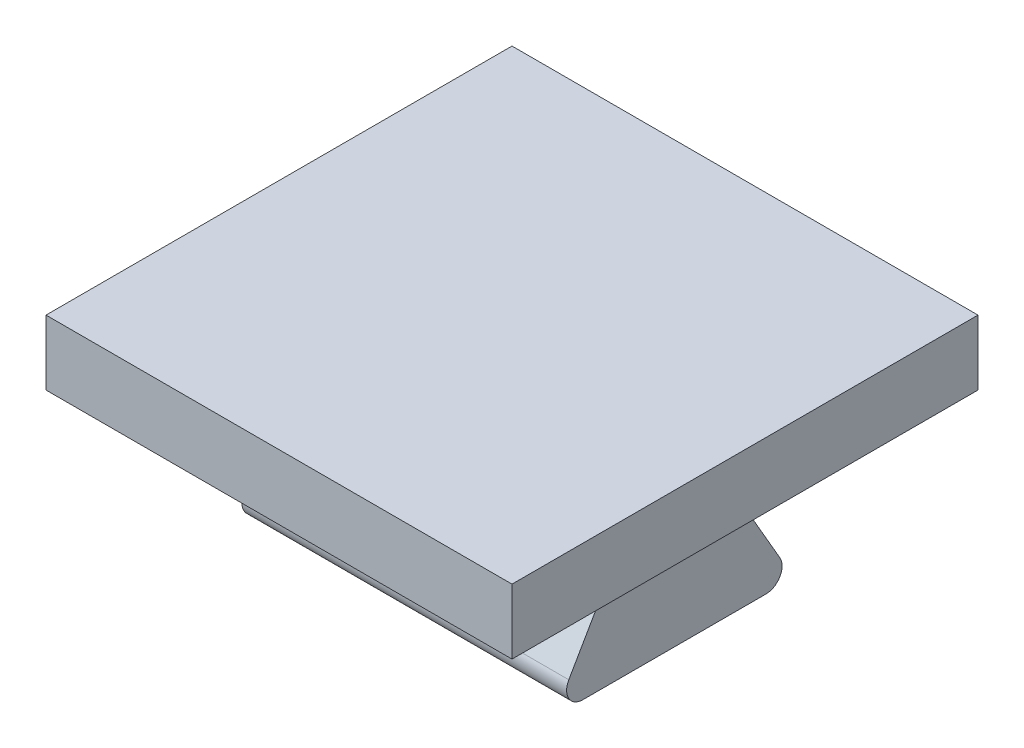
SolidWorks part; units mm, degrees
ref_plane "Front Plane" through (0, 0, 0) normal (0, 0, 1) x (1, 0, 0)
ref_plane "Top Plane" through (0, 0, 0) normal (0, 1, 0) x (1, 0, 0)
ref_plane "Right Plane" through (0, 0, 0) normal (1, 0, 0) x (0, 0, -1)
sketch "Sketch2" plane through (0, 0, 0) normal (0, 1, 0) x (1, 0, 0)
  line L1 (-7.175, -7.175) -> (7.175, -7.175)
  line L2 (-7.175, -7.175) -> (-7.175, 7.175)
  line L3 (-7.175, 7.175) -> (7.175, 7.175)
  line L4 (7.175, -7.175) -> (7.175, 7.175)
  line L5 (-7.175, -7.175) -> (7.175, 7.175) construction
  line L6 (-7.175, 7.175) -> (7.175, -7.175) construction
  point P1 (0, 0)
  dimension "D1" = 14.35
extrude "Boss-Extrude1" add sketch "Sketch2" along normal blind 3
sketch "Sketch3" plane through (0, 0, 0) normal (1, 0, 0) x (0, 0, -1)
  line L0 (-1.75, 0) -> (1.75, 0)
  line L1 (-7.175, 0) -> (7.175, 0) construction
  line L2 (1.75, 0) -> (3.6841, -3.35)
  line L3 (3.6841, -3.35) -> (-3.6841, -3.35)
  line L4 (0, -3.35) -> (0, 0) construction
  line L5 (-1.75, 0) -> (-3.6841, -3.35)
  dimension "D1" = 1.75
  dimension "D2" = 60
  dimension "D3" = 3.35
extrude "Boss-Extrude2" add sketch "Sketch3" along normal mid plane 10
sketch "Sketch4" plane through (0, 0, 0) normal (0, -1, 0) x (1, 0, 0)
  line L0 (5, 3.6841) -> (5, -3.6841) construction
  line L1 (-7.175, -7.175) -> (7.175, -7.175)
  line L2 (-7.175, -7.175) -> (-7.175, 7.175)
  line L3 (-7.175, 7.175) -> (7.175, 7.175)
  line L4 (7.175, -7.175) -> (7.175, 7.175)
  line L5 (-7.175, -7.175) -> (7.175, 7.175) construction
  line L6 (-7.175, 7.175) -> (7.175, -7.175) construction
  line L7 (-5, -3.6841) -> (5, -3.6841)
  line L8 (-5, -3.6841) -> (-5, 3.6841)
  line L9 (-5, 3.6841) -> (5, 3.6841)
  line L10 (5, -3.6841) -> (5, 3.6841)
  line L11 (-5, -3.6841) -> (5, 3.6841) construction
  line L12 (-5, 3.6841) -> (5, -3.6841) construction
  line L13 (5, 3.6841) -> (-5, 3.6841) construction
  point P0 (0, 0)
  point P7 (0, 0)
extrude "Cut-Extrude1" cut sketch "Sketch4" against normal blind 1
fillet "Fillet1" radius 0.5 4 edges at (0, 0, 1.75) (0, 0, -1.75) (0, -3.35, 3.6841) (0, -3.35, -3.6841)
